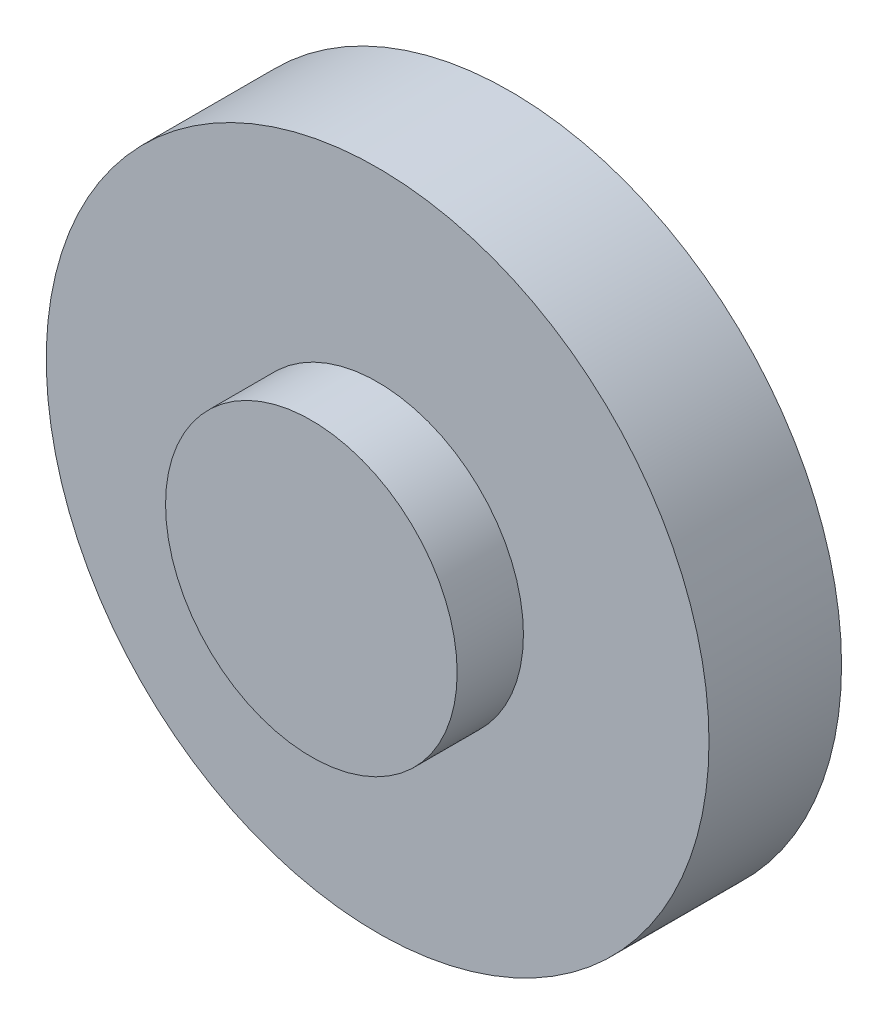
SolidWorks part; units mm, degrees
ref_plane "Front Plane" through (0, 0, 0) normal (0, 0, 1) x (1, 0, 0)
ref_plane "Top Plane" through (0, 0, 0) normal (0, 1, 0) x (1, 0, 0)
ref_plane "Right Plane" through (0, 0, 0) normal (1, 0, 0) x (0, 0, -1)
sketch "Sketch1" plane through (0, 0, 0) normal (0, 0, 1) x (1, 0, 0)
  circle A0 centre (0, 0) radius 25
  dimension "D1" = 50
extrude "Boss-Extrude1" add sketch "Sketch1" along normal blind 10
sketch "Sketch3" plane through (0, 0, 10) normal (0, 0, 1) x (1, 0, 0)
  circle A0 centre (0, 0) radius 11
  dimension "D1" = 22
extrude "Boss-Extrude2" add sketch "Sketch3" along normal blind 5
